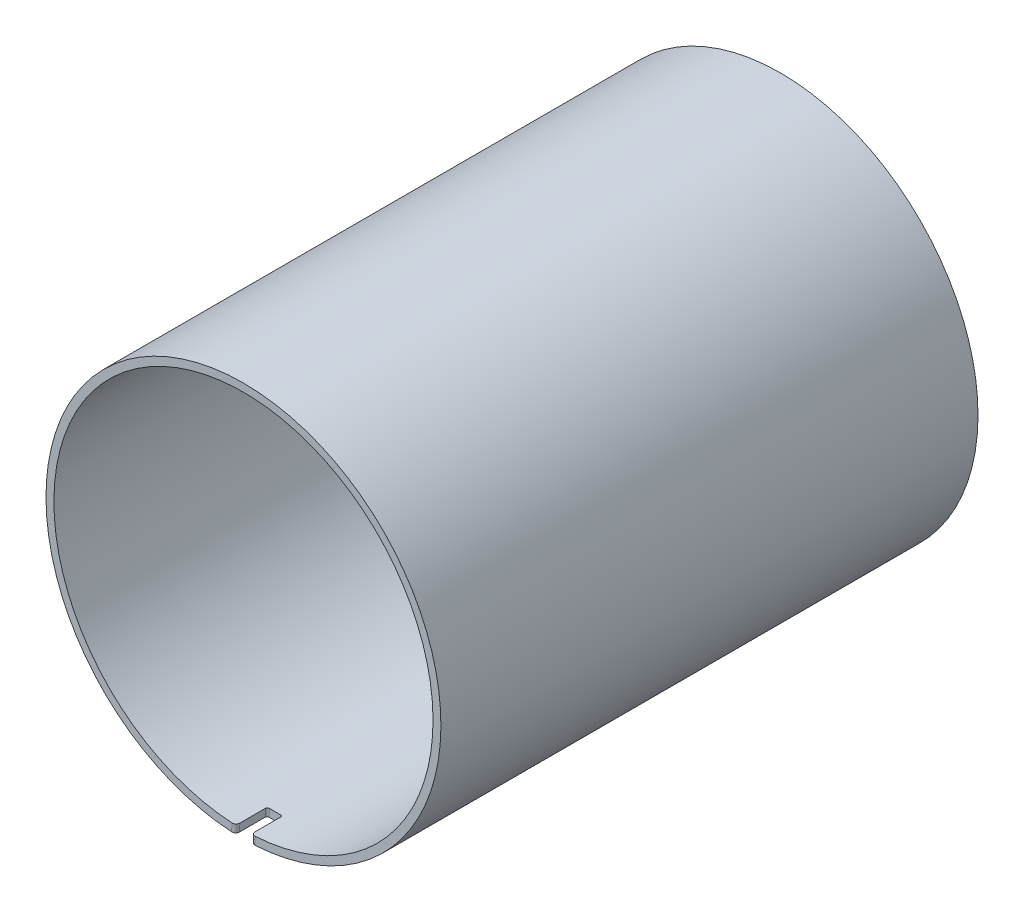
SolidWorks part; units mm, degrees
ref_plane "Спереди" through (0, 0, 0) normal (0, 0, 1) x (1, 0, 0)
ref_plane "Сверху" through (0, 0, 0) normal (0, 1, 0) x (1, 0, 0)
ref_plane "Справа" through (0, 0, 0) normal (1, 0, 0) x (0, 0, -1)
sketch "Эскиз1" plane through (0, 0, 0) normal (0, 0, 1) x (1, 0, 0)
  circle A0 centre (0, 0) radius 50
  circle A1 centre (0, 0) radius 48
  dimension "D1" = 100
  dimension "D2" = 2
extrude "Бобышка-Вытянуть1" add sketch "Эскиз1" along normal blind 136
sketch "Эскиз3" plane through (0, 0, 136) normal (0, 0, 1) x (1, 0, 0)
  line L0 (0, 0) -> (0, -53.3234) construction
  line L1 (-1.92, -47.9616) -> (-2, -49.96)
  line L2 (1.92, -47.9616) -> (2, -49.96)
  circle A0 centre (0, 0) radius 50 construction
  circle A1 centre (0, 0) radius 48 construction
  arc A2 (-2, -49.96) -> (2, -49.96) centre (0, 0) ccw
  arc A3 (-1.92, -47.9616) -> (1.92, -47.9616) centre (0, 0) ccw
  dimension "D1" = 4
extrude "Вырез-Вытянуть1" cut sketch "Эскиз3" against normal blind 8
ref_plane "Плоскость1" through (0, 0, 68) normal (0, 0, 1) x (1, 0, 0)
mirror "Зеркальное отражение3" about plane through (0, 0, 68) normal (0, 0, 1) of "Вырез-Вытянуть1"
fillet "Скругление1" radius 0.5 4 edges at (1.96, -48.9608, 128) (-1.96, -48.9608, 128) (1.96, -48.9608, 8) (-1.96, -48.9608, 8)
fillet "Скругление2" radius 1 4 edges at (1.96, -48.9608, 136) (-1.96, -48.9608, 136) (-1.96, -48.9608, 0) (1.96, -48.9608, 0)
